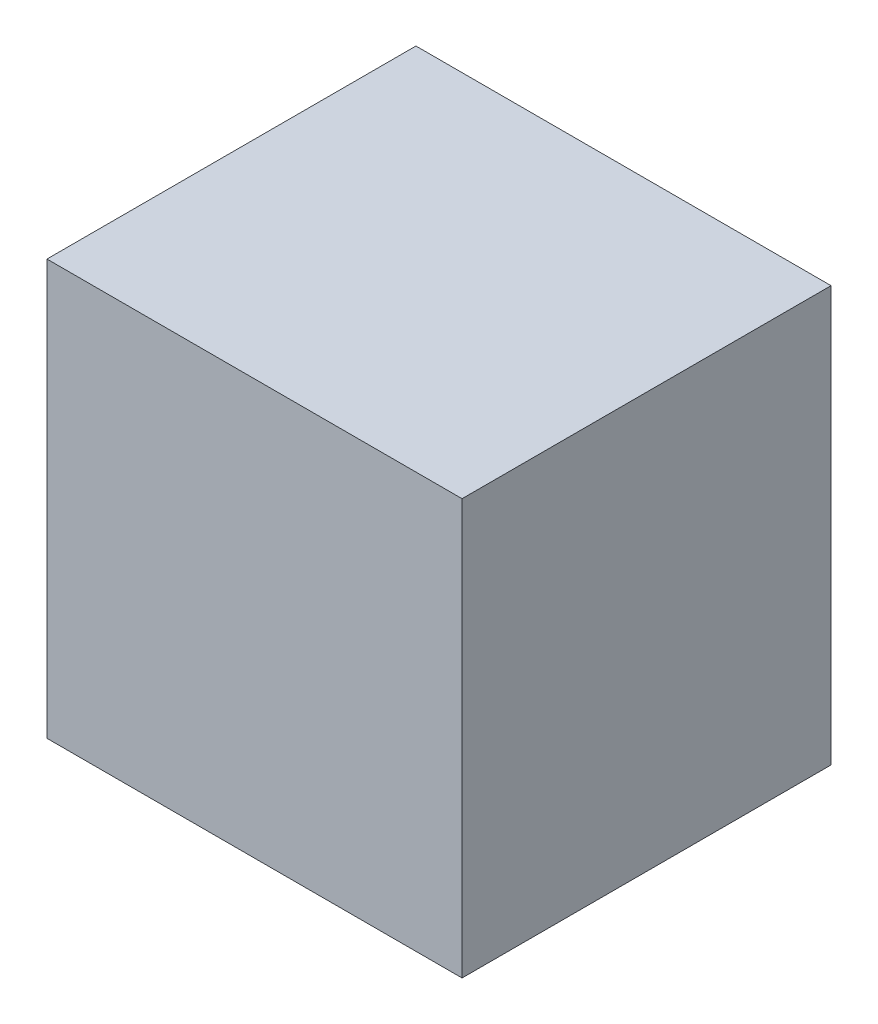
SolidWorks part; units mm, degrees
material "Air"
ref_plane "Front Plane" through (0, 0, 0) normal (0, 0, 1) x (1, 0, 0)
ref_plane "Top Plane" through (0, 0, 0) normal (0, 1, 0) x (1, 0, 0)
ref_plane "Right Plane" through (0, 0, 0) normal (1, 0, 0) x (0, 0, -1)
sketch "Sketch1" plane through (0, 0, 0) normal (0, 0, 1) x (1, 0, 0)
  line L1 (-685.8, 685.8) -> (685.8, 685.8)
  line L2 (-685.8, 685.8) -> (-685.8, -685.8)
  line L3 (-685.8, -685.8) -> (685.8, -685.8)
  line L4 (685.8, 685.8) -> (685.8, -685.8)
  line L5 (-685.8, 685.8) -> (685.8, -685.8) construction
  line L6 (-685.8, -685.8) -> (685.8, 685.8) construction
  point P0 (0, 0)
  dimension "D1" = 1371.6
  dimension "D2" = 1371.6
extrude "Boss-Extrude1" add sketch "Sketch1" along normal blind 1219.2
